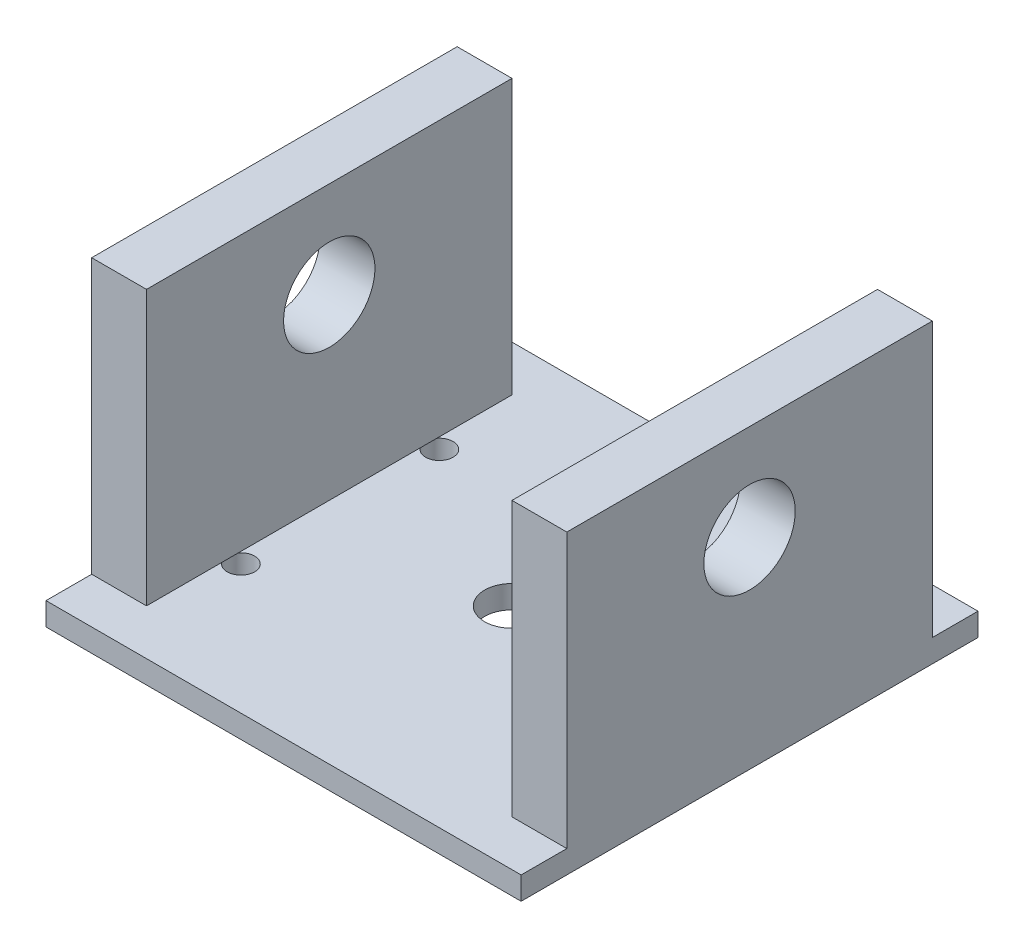
SolidWorks part; units mm, degrees
ref_plane "Front Plane" through (0, 0, 0) normal (0, 0, 1) x (1, 0, 0)
ref_plane "Top Plane" through (0, 0, 0) normal (0, 1, 0) x (1, 0, 0)
ref_plane "Right Plane" through (0, 0, 0) normal (1, 0, 0) x (0, 0, -1)
sketch "Sketch1" plane through (0, 0, 0) normal (0, 1, 0) x (1, 0, 0)
  line L0 (0, 0) -> (0, 19) construction
  line L1 (52, 50) -> (-52, 50)
  line L2 (52, 50) -> (52, -50)
  line L3 (52, -50) -> (-52, -50)
  line L4 (-52, 50) -> (-52, -50)
  line L5 (0, 0) -> (16.7611, 0) construction
  circle A0 centre (-37.62, -21.72) radius 3
  circle A1 centre (37.62, -21.72) radius 3
  circle A2 centre (37.62, 21.72) radius 3
  circle A3 centre (-37.62, 21.72) radius 3
  circle A4 centre (0, 0) radius 6
  point P0 (0, 0)
  point P13 (52, 0)
  point P14 (0, -50)
  dimension "D3" = 37.62
  dimension "D4" = 21.72
  dimension "D5" = 12
  dimension "D1" = 104
  dimension "D2" = 100
extrude "Boss-Extrude1" add sketch "Sketch1" along normal blind 5
sketch "Sketch2" plane through (0, 5, 0) normal (0, 1, 0) x (1, 0, 0)
  line L0 (0, 0) -> (-40, 0) construction
  line L1 (-52, 50) -> (-52, -50) construction
  line L2 (-52, -40) -> (-40, -40)
  line L3 (-52, 40) -> (-40, 40)
  line L4 (-52, 40) -> (-52, -40)
  line L5 (0, 0) -> (0, 18.4204) construction
  line L6 (-40, 40) -> (-40, -40)
  line L7 (40, 40) -> (40, -40)
  line L8 (52, 40) -> (52, -40)
  line L9 (52, 40) -> (40, 40)
  line L10 (52, -40) -> (40, -40)
  point P10 (-52, 0)
  point P15 (52, 0)
  dimension "D1" = 12
  dimension "D2" = 40
extrude "Boss-Extrude2" add sketch "Sketch2" along normal blind 60
sketch "Sketch3" plane through (-52, 0, 0) normal (-1, 0, 0) x (0, 0, 1)
  line L0 (0, 65) -> (0, 0) construction
  line L2 (-40, 65) -> (40, 65) construction
  line L5 (-50, 0) -> (50, 0) construction
  circle A0 centre (0, 44) radius 10
  point P7 (0, 42.5527)
  dimension "D1" = 20
  dimension "D2" = 44
extrude "Cut-Extrude1" cut sketch "Sketch3" against normal through all both and the other way through all
